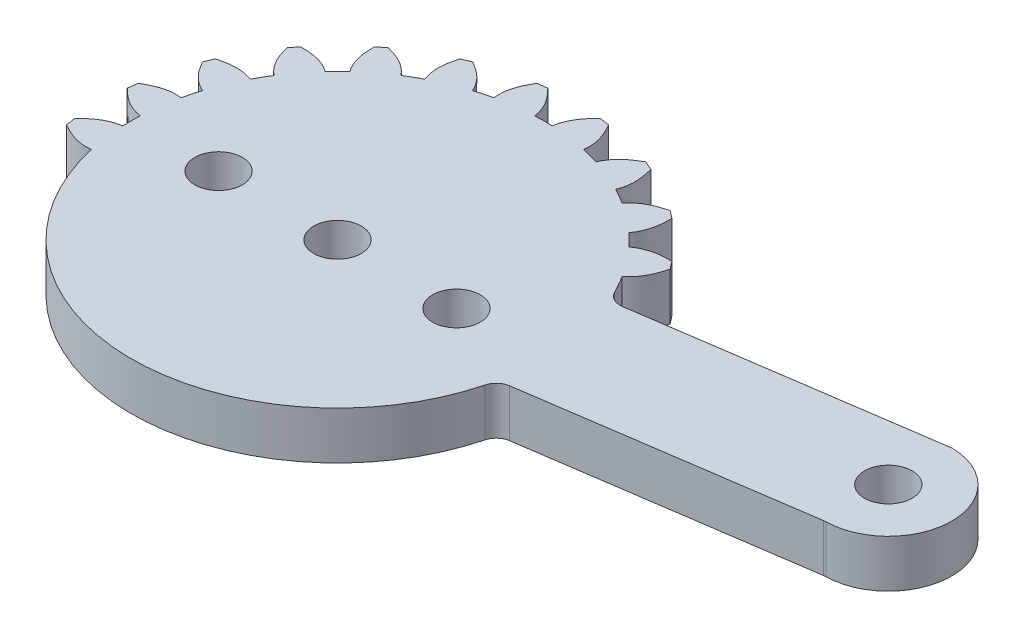
SolidWorks part; units mm, degrees
ref_plane "Front Plane" through (0, 0, 0) normal (0, 0, 1) x (1, 0, 0)
ref_plane "Top Plane" through (0, 0, 0) normal (0, 1, 0) x (1, 0, 0)
ref_plane "Right Plane" through (0, 0, 0) normal (1, 0, 0) x (0, 0, -1)
sketch "Sketch1" plane through (0, 0, 0) normal (0, 1, 0) x (1, 0, 0)
  line L0 (12.6327, 5.3405) -> (30.6525, 7.9886)
  line L1 (0, 0) -> (11.9003, 9.1314) construction
  line L2 (0, 0) -> (19.2179, 25.0452) construction
  line L3 (0, 0) -> (9.1924, 9.1924) construction
  line L5 (30.6617, -0.01) -> (13.4007, -2.5466)
  circle A2 centre (0, 0) radius 1.5
  circle A3 centre (7.5, 0) radius 1.5
  circle A4 centre (-7.5, 0) radius 1.5
  arc A5 (-12.4035, -3.8928) -> (12.5785, -3.2834) centre (0, 0) ccw
  circle A6 centre (30.73, 4) radius 1.5
  arc A8 (11.5954, 5.8777) -> (10.9732, 6.9706) centre (0, 0) ccw
  arc A9 (30.7917, 0.0005) -> (30.8205, 7.999) centre (30.73, 4) ccw
  arc A10 (30.6617, -0.01) -> (30.7917, 0.0005) centre (30.8071, -0.9994) cw
  arc A11 (30.6525, 7.9886) -> (30.8205, 7.999) centre (30.7979, 6.9992) cw
  arc A12 (12.6327, 5.3405) -> (11.5954, 5.8777) centre (12.4873, 6.3299) cw
  arc A13 (12.5785, -3.2834) -> (13.4007, -2.5466) centre (13.5461, -3.536) cw
  spline S0 degree 3 poles (9.5731, 8.7952) (10.2501, 9.2991) (10.982, 9.3793) (11.7091, 9.3754) knots 0 0 0 0 0.58557 0.58557 0.58557 0.58557
  spline S1 degree 2 poles (11.7091, 9.3754) (11.9028, 9.1334) (12.0865, 8.8835) knots 0 0 0 1 1 1
  spline S2 degree 3 poles (10.9732, 6.9706) (11.6352, 7.494) (11.9021, 8.1802) (12.0865, 8.8835) knots 0 0 0 0 0.58557 0.58557 0.58557 0.58557
  spline S4 degree 3 poles (8.7952, 9.5731) (9.2991, 10.2501) (9.3793, 10.982) (9.3754, 11.7091) knots 0 0 0 0 0.58557 0.58557 0.58557 0.58557
  spline S5 degree 2 poles (8.8835, 12.0865) (9.1334, 11.9028) (9.3754, 11.7091) knots 0 0 0 1 1 1
  spline S6 degree 3 poles (6.9706, 10.9732) (7.494, 11.6352) (8.1802, 11.9021) (8.8835, 12.0865) knots 0 0 0 0 0.58557 0.58557 0.58557 0.58557
  spline S7 degree 3 poles (6.0178, 11.5233) (6.3294, 12.3076) (6.2174, 13.0353) (6.0254, 13.7366) knots 0 0 0 0 0.58557 0.58557 0.58557 0.58557
  spline S8 degree 2 poles (5.4526, 13.9739) (5.7415, 13.8612) (6.0254, 13.7366) knots 0 0 0 1 1 1
  spline S9 degree 3 poles (3.893, 12.4034) (4.2273, 13.1783) (4.821, 13.6137) (5.4526, 13.9739) knots 0 0 0 0 0.58557 0.58557 0.58557 0.58557
  spline S10 degree 3 poles (2.8303, 12.6882) (2.9283, 13.5264) (2.6318, 14.2003) (2.2648, 14.828) knots 0 0 0 0 0.58557 0.58557 0.58557 0.58557
  spline S11 degree 2 poles (1.6501, 14.909) (1.9583, 14.8748) (2.2648, 14.828) knots 0 0 0 1 1 1
  spline S12 degree 3 poles (0.5501, 12.9884) (0.6724, 13.8234) (1.1332, 14.3976) (1.6501, 14.909) knots 0 0 0 0 0.58557 0.58557 0.58557 0.58557
  spline S13 degree 3 poles (-0.5501, 12.9884) (-0.6724, 13.8234) (-1.1332, 14.3976) (-1.6501, 14.909) knots 0 0 0 0 0.58557 0.58557 0.58557 0.58557
  spline S14 degree 2 poles (-2.2648, 14.828) (-1.9583, 14.8748) (-1.6501, 14.909) knots 0 0 0 1 1 1
  spline S15 degree 3 poles (-2.8303, 12.6882) (-2.9283, 13.5264) (-2.6318, 14.2003) (-2.2648, 14.828) knots 0 0 0 0 0.58557 0.58557 0.58557 0.58557
  spline S16 degree 3 poles (-3.893, 12.4034) (-4.2273, 13.1783) (-4.821, 13.6137) (-5.4526, 13.9739) knots 0 0 0 0 0.58557 0.58557 0.58557 0.58557
  spline S17 degree 2 poles (-6.0254, 13.7366) (-5.7415, 13.8612) (-5.4526, 13.9739) knots 0 0 0 1 1 1
  spline S18 degree 3 poles (-6.0178, 11.5233) (-6.3294, 12.3076) (-6.2174, 13.0353) (-6.0254, 13.7366) knots 0 0 0 0 0.58557 0.58557 0.58557 0.58557
  spline S19 degree 3 poles (-6.9706, 10.9732) (-7.494, 11.6352) (-8.1802, 11.9021) (-8.8835, 12.0865) knots 0 0 0 0 0.58557 0.58557 0.58557 0.58557
  spline S20 degree 2 poles (-9.3754, 11.7091) (-9.1334, 11.9028) (-8.8835, 12.0865) knots 0 0 0 1 1 1
  spline S21 degree 3 poles (-8.7952, 9.5731) (-9.2991, 10.2501) (-9.3793, 10.982) (-9.3754, 11.7091) knots 0 0 0 0 0.58557 0.58557 0.58557 0.58557
  spline S22 degree 3 poles (-9.5731, 8.7952) (-10.2501, 9.2991) (-10.982, 9.3793) (-11.7091, 9.3754) knots 0 0 0 0 0.58557 0.58557 0.58557 0.58557
  spline S23 degree 2 poles (-12.0865, 8.8835) (-11.9028, 9.1334) (-11.7091, 9.3754) knots 0 0 0 1 1 1
  spline S24 degree 3 poles (-10.9732, 6.9706) (-11.6352, 7.494) (-11.9021, 8.1802) (-12.0865, 8.8835) knots 0 0 0 0 0.58557 0.58557 0.58557 0.58557
  spline S25 degree 3 poles (-11.5233, 6.0178) (-12.3076, 6.3294) (-13.0353, 6.2174) (-13.7366, 6.0254) knots 0 0 0 0 0.58557 0.58557 0.58557 0.58557
  spline S26 degree 2 poles (-13.9739, 5.4526) (-13.8612, 5.7415) (-13.7366, 6.0254) knots 0 0 0 1 1 1
  spline S27 degree 3 poles (-12.4034, 3.893) (-13.1783, 4.2273) (-13.6137, 4.821) (-13.9739, 5.4526) knots 0 0 0 0 0.58557 0.58557 0.58557 0.58557
  spline S28 degree 3 poles (-12.6882, 2.8303) (-13.5264, 2.9283) (-14.2003, 2.6318) (-14.828, 2.2648) knots 0 0 0 0 0.58557 0.58557 0.58557 0.58557
  spline S29 degree 2 poles (-14.909, 1.6501) (-14.8748, 1.9583) (-14.828, 2.2648) knots 0 0 0 1 1 1
  spline S30 degree 3 poles (-12.9884, 0.5501) (-13.8234, 0.6724) (-14.3976, 1.1332) (-14.909, 1.6501) knots 0 0 0 0 0.58557 0.58557 0.58557 0.58557
  spline S31 degree 3 poles (-12.9884, -0.5501) (-13.8234, -0.6724) (-14.3976, -1.1332) (-14.909, -1.6501) knots 0 0 0 0 0.58557 0.58557 0.58557 0.58557
  spline S32 degree 2 poles (-14.828, -2.2648) (-14.8748, -1.9583) (-14.909, -1.6501) knots 0 0 0 1 1 1
  spline S33 degree 3 poles (-12.6882, -2.8303) (-13.5264, -2.9283) (-14.2003, -2.6318) (-14.828, -2.2648) knots 0 0 0 0 0.58557 0.58557 0.58557 0.58557
  spline S34 degree 2 poles (-12.4035, -3.8928) (-12.5684, -3.3677) (-12.6882, -2.8303) knots 0 0 0 0.029411 0.029411 0.029411
  spline S35 degree 3 poles (-12.9884, -0.5501) (-13.0039, -0.1835) (-13.0039, 0.1835) (-12.9884, 0.5501) knots 0.090903 0.090903 0.090903 0.090903 0.120321 0.120321 0.120321 0.120321
  spline S36 degree 3 poles (-12.6882, 2.8303) (-12.6083, 3.1884) (-12.5134, 3.5429) (-12.4034, 3.893) knots 0.181813 0.181813 0.181813 0.181813 0.211231 0.211231 0.211231 0.211231
  spline S37 degree 3 poles (-11.5233, 6.0178) (-11.3535, 6.3431) (-11.17, 6.6609) (-10.9732, 6.9706) knots 0.272722 0.272722 0.272722 0.272722 0.302141 0.302141 0.302141 0.302141
  spline S38 degree 3 poles (-9.5731, 8.7952) (-9.3249, 9.0654) (-9.0654, 9.3249) (-8.7952, 9.5731) knots 0.363632 0.363632 0.363632 0.363632 0.39305 0.39305 0.39305 0.39305
  spline S39 degree 3 poles (-6.9706, 10.9732) (-6.6609, 11.17) (-6.3431, 11.3535) (-6.0178, 11.5233) knots 0.454542 0.454542 0.454542 0.454542 0.48396 0.48396 0.48396 0.48396
  spline S40 degree 3 poles (-3.893, 12.4034) (-3.5429, 12.5134) (-3.1884, 12.6083) (-2.8303, 12.6882) knots 0.545452 0.545452 0.545452 0.545452 0.57487 0.57487 0.57487 0.57487
  spline S41 degree 3 poles (-0.5501, 12.9884) (-0.1835, 13.0039) (0.1835, 13.0039) (0.5501, 12.9884) knots 0.636361 0.636361 0.636361 0.636361 0.665779 0.665779 0.665779 0.665779
  spline S42 degree 3 poles (2.8303, 12.6882) (3.1884, 12.6083) (3.5429, 12.5134) (3.893, 12.4034) knots 0.727271 0.727271 0.727271 0.727271 0.756689 0.756689 0.756689 0.756689
  spline S43 degree 3 poles (6.0178, 11.5233) (6.3431, 11.3535) (6.6609, 11.17) (6.9706, 10.9732) knots 0.818181 0.818181 0.818181 0.818181 0.847599 0.847599 0.847599 0.847599
  spline S44 degree 3 poles (8.7952, 9.5731) (9.0655, 9.3249) (9.325, 9.0653) (9.5731, 8.7952) knots 0.90909 0.90909 0.90909 0.90909 0.938508 0.938508 0.938508 0.938508
  point P32 (30.73, 0)
  point P74 (0, 0)
  point P77 (30.73, 8)
  point P98 (0, 0)
  dimension "D1" = 3
  dimension "D4" = 23.23
  dimension "D5" = 8
  dimension "D15" = 3
  dimension "D7" = 1
  dimension "D2" = 7.5
  dimension "D3" = 15
  dimension "D6" = 4
extrude "Boss-Extrude1" add sketch "Sketch1" along normal blind 3
scale "Ölçek1" bodies to scale 101 scale about centroid uniform scaling yes scale factor 2
